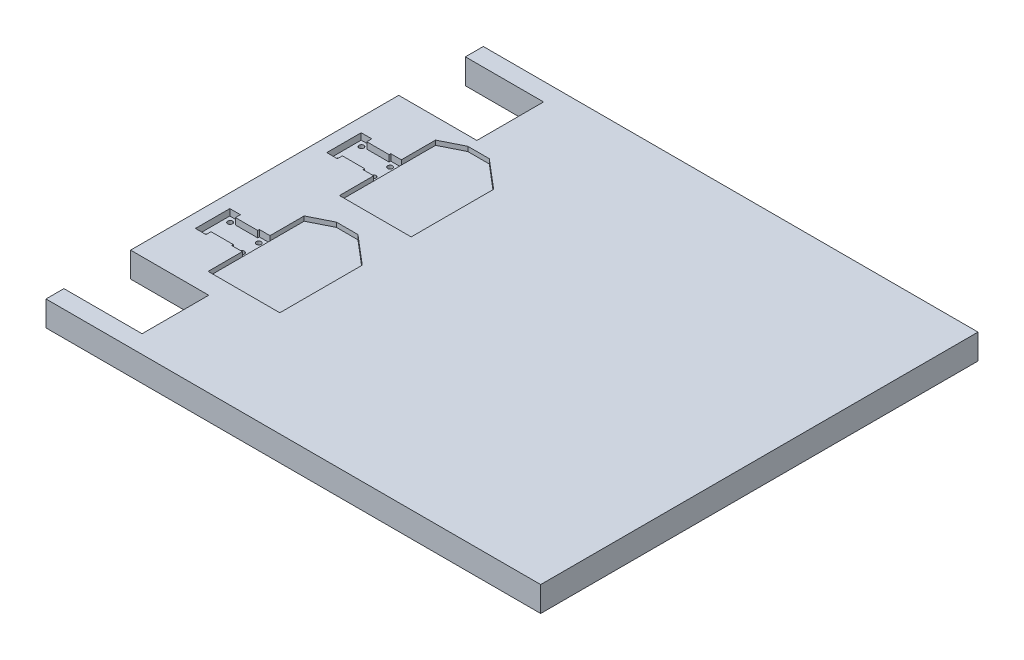
SolidWorks part; units mm, degrees
ref_plane "Front Plane" through (0, 0, 0) normal (0, 0, 1) x (1, 0, 0)
ref_plane "Top Plane" through (0, 0, 0) normal (0, 1, 0) x (1, 0, 0)
ref_plane "Right Plane" through (0, 0, 0) normal (1, 0, 0) x (0, 0, -1)
sketch "Sketch1" plane through (0, 0, 0) normal (0, 1, 0) x (1, 0, 0)
  line L0 (27.7243, -2.5797) -> (27.7243, 43.9203)
  line L2 (-26.7757, 230.9203) -> (-26.7757, 43.9203)
  line L4 (318.2243, 289.9203) -> (318.2243, -15.0797)
  line L5 (27.7243, 43.9203) -> (-26.7757, 43.9203)
  line L6 (-26.7757, 230.9203) -> (27.7243, 230.9203)
  line L7 (27.7243, 230.9203) -> (27.7243, 277.4203)
  line L9 (-26.7757, 289.9203) -> (-26.7757, 277.4203)
  line L10 (-26.7757, 277.4203) -> (27.7243, 277.4203)
  line L12 (-26.7757, -15.0797) -> (-26.7757, -2.5797)
  line L14 (-26.7757, -2.5797) -> (27.7243, -2.5797)
  line L15 (-26.7757, 289.9203) -> (318.2243, 289.9203)
  line L16 (318.2243, -15.0797) -> (-26.7757, -15.0797)
  dimension "D1" = 345
  dimension "D2" = 345
  dimension "D3" = 305
  dimension "D4" = 59
  dimension "D5" = 59
  dimension "D6" = 187
  dimension "D7" = 12.5
  dimension "D8" = 12.5
  dimension "D9" = 54.5
  dimension "D10" = 54.5
  dimension "D11" = 270
  dimension "D12" = 270
  dimension "D13" = 270
  dimension "D14" = 270
  dimension "D15" = 90
  dimension "D16" = 90
  dimension "D17" = 270
  dimension "D18" = 270
  dimension "D19" = 90
  dimension "D20" = 90
  dimension "D21" = 270
  dimension "D22" = 270
  dimension "D23" = 54.5
  dimension "D24" = 46.5
  dimension "D25" = 54.5
  dimension "D26" = 46.5
extrude "Boss-Extrude1" add sketch "Sketch1" along normal blind 17.5
sketch "Sketch2" plane through (0, 17.5, 0) normal (0, 1, 0) x (1, 0, 0)
  line L0 (-13.2757, 91.6103) -> (9.0943, 91.6103) construction
  line L2 (27.7243, 230.9203) -> (-26.7757, 230.9203) construction
  line L3 (-26.7757, 230.9203) -> (-26.7757, 43.9203) construction
  line L4 (-13.2757, 183.2303) -> (9.0943, 183.2303) construction
  line L5 (5.6943, 191.7453) -> (-9.8757, 191.7453)
  line L6 (-9.8757, 174.7153) -> (5.6943, 174.7153)
  line L7 (13.0943, 192.8903) -> (13.0943, 173.5703)
  line L8 (-17.2757, 195.2303) -> (-17.2757, 171.2303)
  line L9 (-17.2757, 195.2303) -> (-9.8757, 195.2303)
  line L10 (-9.8757, 195.2303) -> (-9.8757, 191.7453)
  line L11 (13.0943, 192.8903) -> (5.6943, 192.8903)
  line L12 (5.6943, 192.8903) -> (5.6943, 191.7453)
  line L13 (13.0943, 173.5703) -> (5.6943, 173.5703)
  line L14 (5.6943, 173.5703) -> (5.6943, 174.7153)
  line L15 (-17.2757, 171.2303) -> (-9.8757, 171.2303)
  line L16 (-9.8757, 171.2303) -> (-9.8757, 174.7153)
  line L28 (5.6943, 100.1253) -> (-9.8757, 100.1253)
  line L29 (-9.8757, 83.0953) -> (5.6943, 83.0953)
  line L30 (13.0943, 101.2703) -> (13.0943, 81.9503)
  line L31 (-17.2757, 103.6103) -> (-17.2757, 79.6103)
  line L32 (-17.2757, 103.6103) -> (-9.8757, 103.6103)
  line L33 (-9.8757, 103.6103) -> (-9.8757, 100.1253)
  line L34 (13.0943, 101.2703) -> (5.6943, 101.2703)
  line L35 (5.6943, 101.2703) -> (5.6943, 100.1253)
  line L36 (13.0943, 81.9503) -> (5.6943, 81.9503)
  line L37 (5.6943, 81.9503) -> (5.6943, 83.0953)
  line L38 (-17.2757, 79.6103) -> (-9.8757, 79.6103)
  line L39 (-9.8757, 79.6103) -> (-9.8757, 83.0953)
  line L40 (-26.7757, 43.9203) -> (27.7243, 43.9203) construction
  circle A1 centre (-13.2757, 191.4203) radius 1.5
  circle A2 centre (-13.2757, 175.0403) radius 1.5
  circle A3 centre (9.0943, 189.0503) radius 1.5
  circle A4 centre (9.0943, 177.4103) radius 1.5
  circle A9 centre (-13.2757, 99.8003) radius 1.5
  circle A10 centre (-13.2757, 83.4203) radius 1.5
  circle A11 centre (9.0943, 97.4303) radius 1.5
  circle A12 centre (9.0943, 85.7903) radius 1.5
  point P0 (-13.2757, 191.4203)
  point P5 (-13.2757, 175.0403)
  point P6 (9.0943, 189.0503)
  point P7 (9.0943, 177.4103)
  point P12 (-2.0907, 174.7153)
  point P15 (-2.0907, 183.2303)
  point P16 (-2.0907, 191.7453)
  point P21 (-17.2757, 183.2303)
  point P23 (13.0943, 183.2303)
  point P34 (-13.2757, 99.8003)
  point P36 (-13.2757, 83.4203)
  point P37 (9.0943, 97.4303)
  point P38 (9.0943, 85.7903)
  point P43 (-2.0907, 83.0953)
  point P46 (-2.0907, 91.6103)
  point P47 (-2.0907, 100.1253)
  point P52 (-17.2757, 91.6103)
  point P54 (13.0943, 91.6103)
  dimension "D24" = 3
  dimension "D25" = 3
  dimension "D26" = 3
  dimension "D27" = 3
  dimension "D38" = 15.57
  dimension "D39" = 15.57
  dimension "D40" = 0
  dimension "D41" = 0
  dimension "D48" = 3
  dimension "D49" = 3
  dimension "D50" = 3
  dimension "D51" = 3
  dimension "D1" = 39.5
  dimension "D2" = 13.5
  dimension "D3" = 8.19
  dimension "D4" = 8.19
  dimension "D5" = 22.37
  dimension "D6" = 5.82
  dimension "D7" = 5.82
  dimension "D8" = 22.37
  dimension "D9" = 13.5
  dimension "D10" = 13.5
  dimension "D11" = 22.37
  dimension "D12" = 8.515
  dimension "D13" = 8.515
  dimension "D14" = 15.57
  dimension "D15" = 15.57
  dimension "D16" = 0
  dimension "D17" = 0
  dimension "D18" = 4
  dimension "D19" = 4
  dimension "D20" = 24
  dimension "D21" = 0
  dimension "D22" = 0
  dimension "D23" = 19.32
  dimension "D28" = 4
  dimension "D29" = 8.19
  dimension "D30" = 8.19
  dimension "D31" = 22.37
  dimension "D32" = 5.82
  dimension "D33" = 5.82
  dimension "D34" = 22.37
  dimension "D35" = 22.37
  dimension "D36" = 8.515
  dimension "D37" = 8.515
  dimension "D42" = 4
  dimension "D43" = 4
  dimension "D44" = 24
  dimension "D45" = 0
  dimension "D46" = 0
  dimension "D47" = 19.32
  dimension "D52" = 4
  dimension "D53" = 13.5
  dimension "D54" = 39.5
  dimension "D55" = 4
  dimension "D56" = 4
  dimension "D57" = 3.84
  dimension "D58" = 3.84
  dimension "D59" = 3.84
  dimension "D60" = 3.84
extrude "Cut-Extrude1" cut sketch "Sketch2" against normal blind 4.5
hole_wizard "CSK for M3 Oval Head Machine Screw1" positions "Sketch5" profile "Sketch6" countersink size "M3" standard "ANSI Metric" end condition through all
sketch "Sketch5" plane through (0, 0, 0) normal (0, -1, 0) x (-1, 0, 0)
  point P0 (13.2757, 191.4203)
  point P3 (13.2757, 175.0403)
  point P6 (-9.0943, 177.4103)
  point P9 (-9.0943, 189.0503)
  point P12 (13.2757, 83.4203)
  point P15 (13.2757, 99.8003)
  point P18 (-9.0943, 97.4303)
  point P21 (-9.0943, 85.7903)
sketch "Sketch6" plane through (-13.2757, 0, -191.4203) normal (1, 0, 0) x (0, 0, -1)
  line L0 (0, 0) -> (0, 17.5)
  line L1 (0, 17.5) -> (1.7, 17.5)
  line L2 (1.7, 17.5) -> (1.7, 1.45)
  line L3 (1.7, 1.45) -> (3.15, 0)
  line L5 (3.15, 0) -> (0, 0)
  line L6 (-1.7, 1.45) -> (-3.15, 0) construction
  line L11 (0, -6.35) -> (0, 107.95) construction
  dimension "Thru Hole Dia." = 3.4
  dimension "Thru Hole Depth" = 17.5
  dimension "Near C'Sink Dia." = 6.3
  dimension "Near C'Sink Angle" = 90
sketch "Sketch7" plane through (0, 17.5, 0) normal (0, 1, 0) x (1, 0, 0)
  line L0 (-2.0907, 191.7453) -> (-2.0907, 174.7153) construction
  line L1 (5.6943, 191.7453) -> (-9.8757, 191.7453) construction
  line L2 (-9.8757, 174.7153) -> (5.6943, 174.7153) construction
  line L3 (13.0943, 183.2303) -> (-2.0907, 183.2303) construction
  line L4 (13.0943, 173.5703) -> (13.0943, 192.8903) construction
  line L5 (13.0943, 183.2303) -> (13.0943, 216.7303)
  line L6 (13.0943, 183.2303) -> (13.0943, 149.7303)
  line L7 (13.0943, 149.7303) -> (63.0943, 149.7303)
  line L8 (13.0943, 216.7303) -> (28.0943, 224.2303)
  line L9 (28.0943, 224.2303) -> (43.0943, 224.2303)
  line L10 (43.0943, 224.2303) -> (63.0943, 207.2303)
  line L12 (63.0943, 207.2303) -> (63.0943, 149.7303)
  line L13 (-2.0907, 100.1253) -> (-2.0907, 83.0953) construction
  line L14 (5.6943, 100.1253) -> (-9.8757, 100.1253) construction
  line L15 (13.0943, 91.6103) -> (13.0943, 125.1103)
  line L16 (13.0943, 91.6103) -> (13.0943, 58.1103)
  line L17 (13.0943, 58.1103) -> (63.0943, 58.1103)
  line L18 (13.0943, 125.1103) -> (28.0943, 132.6103)
  line L19 (28.0943, 132.6103) -> (43.0943, 132.6103)
  line L20 (43.0943, 132.6103) -> (63.0943, 115.6103)
  line L21 (63.0943, 115.6103) -> (63.0943, 58.1103)
  line L22 (-9.8757, 83.0953) -> (5.6943, 83.0953) construction
  line L23 (-2.0907, 91.6103) -> (13.0943, 91.6103) construction
  line L24 (13.0943, 81.9503) -> (13.0943, 101.2703) construction
  dimension "D1" = 33.5
  dimension "D2" = 33.5
  dimension "D3" = 50
  dimension "D4" = 15
  dimension "D5" = 7.5
  dimension "D6" = 15
  dimension "D7" = 17
  dimension "D8" = 33.5
  dimension "D9" = 33.5
  dimension "D10" = 50
  dimension "D11" = 15
  dimension "D12" = 7.5
  dimension "D13" = 15
  dimension "D14" = 17
  dimension "D15" = 0
  dimension "D16" = 0
extrude "Cut-Extrude2" cut sketch "Sketch7" against normal blind 3.2
